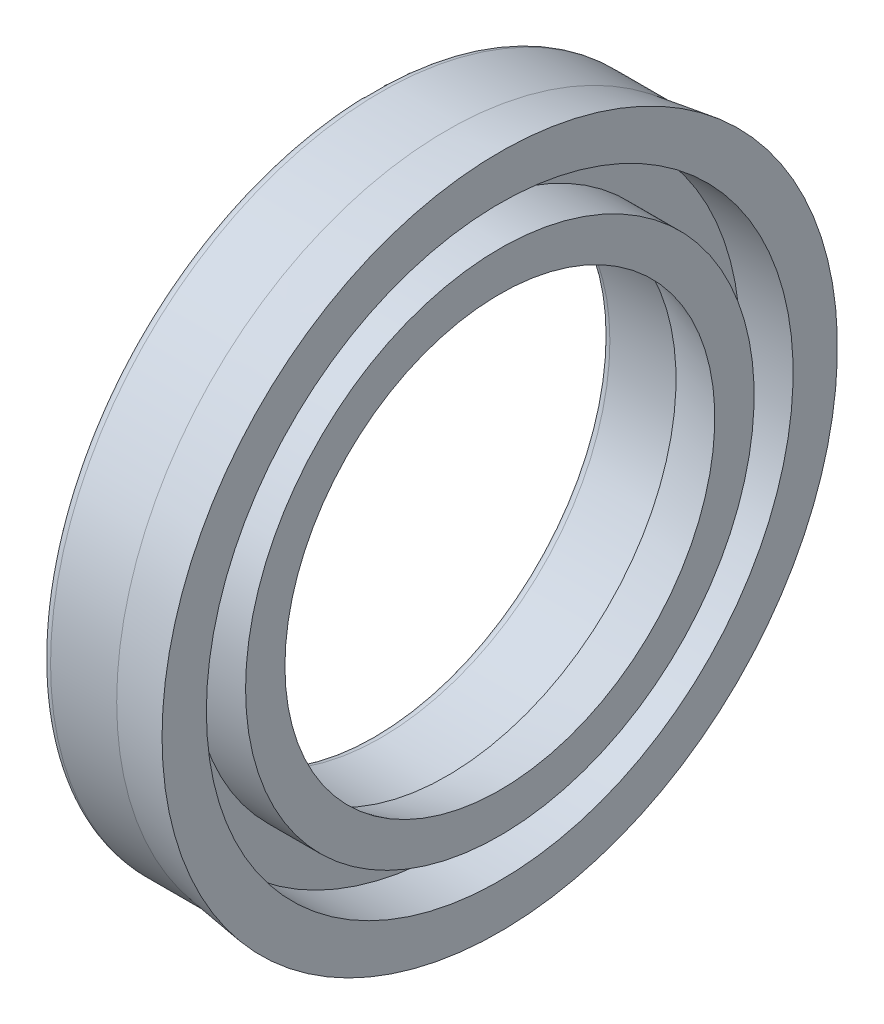
SolidWorks part; units mm, degrees
ref_plane "Front Plane" through (0, 0, 0) normal (0, 0, 1) x (1, 0, 0)
ref_plane "Top Plane" through (0, 0, 0) normal (0, 1, 0) x (1, 0, 0)
ref_plane "Right Plane" through (0, 0, 0) normal (1, 0, 0) x (0, 0, -1)
sketch "Sketch1" plane through (0, 0, 0) normal (0, 0, 1) x (1, 0, 0)
  line L0 (0, 0) -> (41.6404, 0) construction
  line L1 (0, 18) -> (0, 12.5)
  line L2 (0, 12.5) -> (4.1064, 12.5)
  line L3 (4.1064, 12.5) -> (7, 11.7199)
  line L4 (7, 11.7199) -> (7, 13.8658)
  line L5 (7, 13.8658) -> (4.1064, 13.8658)
  line L6 (4.1064, 13.8658) -> (4.1064, 15.9974)
  line L7 (4.1064, 15.9974) -> (6.9937, 15.9974)
  line L8 (6.9937, 15.9974) -> (6.9937, 18)
  line L9 (4.1064, 18) -> (0, 18)
  line L10 (4.1064, 18) -> (6.9937, 18.414)
  line L11 (6.9937, 18.414) -> (6.9937, 18)
  dimension "D1" = 36
  dimension "D2" = 25
  dimension "D3" = 7
revolve "Revolve1" add sketch "Sketch1" angle 360 about L0
fillet "Fillet1" radius 0.5 1 edges at (0, 0, 18)
fillet "Fillet2" radius 0.5 1 edges at (0, 0, 12.5)
